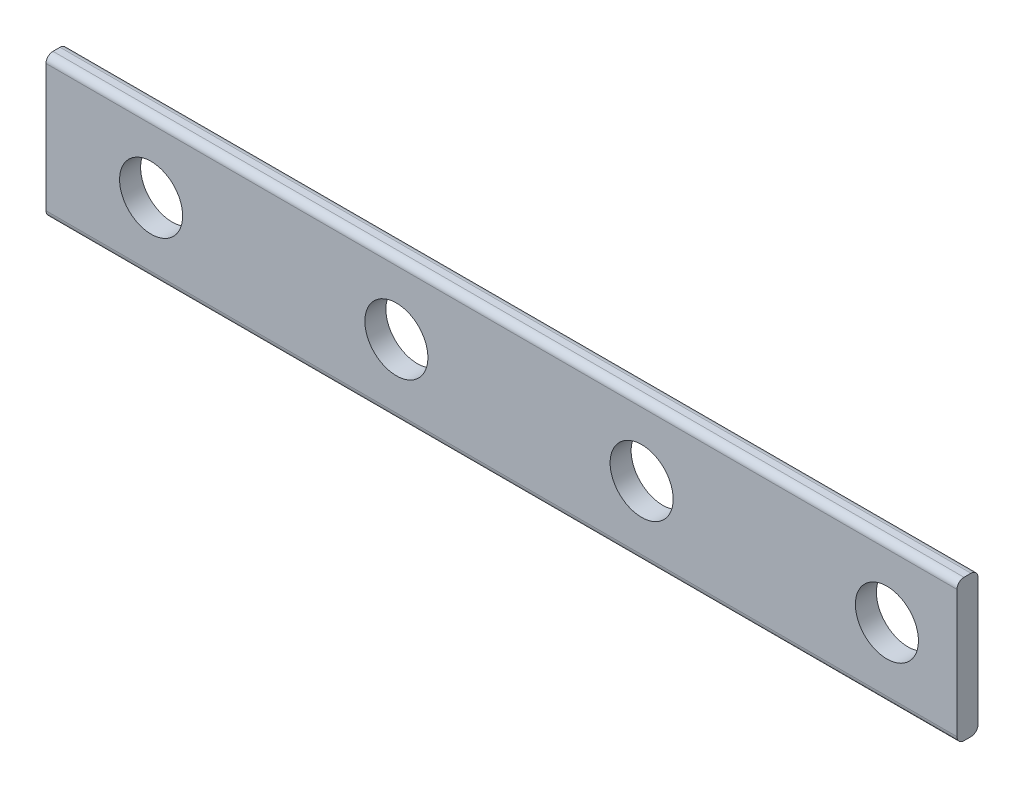
SolidWorks part; units mm, degrees
ref_plane "Front Plane" through (0, 0, 0) normal (0, 0, 1) x (1, 0, 0)
ref_plane "Top Plane" through (0, 0, 0) normal (0, 1, 0) x (1, 0, 0)
ref_plane "Right Plane" through (0, 0, 0) normal (1, 0, 0) x (0, 0, -1)
sketch "Sketch1" plane through (0, 0, 0) normal (0, 0, 1) x (1, 0, 0)
  line L0 (-65, 0) -> (-50, 0) construction
  line L1 (-65, 10.1) -> (65, 10.1)
  line L2 (-65, 10.1) -> (-65, -10.1)
  line L3 (-65, -10.1) -> (65, -10.1)
  line L4 (65, 10.1) -> (65, -10.1)
  line L5 (-65, 10.1) -> (65, -10.1) construction
  line L6 (-65, -10.1) -> (65, 10.1) construction
  line L7 (-50, 0) -> (-15, 0) construction
  line L8 (-15, 0) -> (20, 0) construction
  line L9 (20, 0) -> (55, 0) construction
  circle A0 centre (-50, 0) radius 4.5
  circle A1 centre (-15, 0) radius 4.5
  circle A2 centre (20, 0) radius 4.5
  circle A3 centre (55, 0) radius 4.5
  point P0 (0, 0)
  dimension "D7" = 9
  dimension "D8" = 9
  dimension "D9" = 9
  dimension "D10" = 9
  dimension "D1" = 130
  dimension "D2" = 20.2
  dimension "D3" = 15
  dimension "D4" = 35
  dimension "D5" = 35
  dimension "D6" = 35
extrude "Boss-Extrude1" add sketch "Sketch1" along normal blind 3
fillet "Fillet1" radius 1 4 edges at (0, 10.1, 0) (0, 10.1, 3) (0, -10.1, 0) (0, -10.1, 3)
